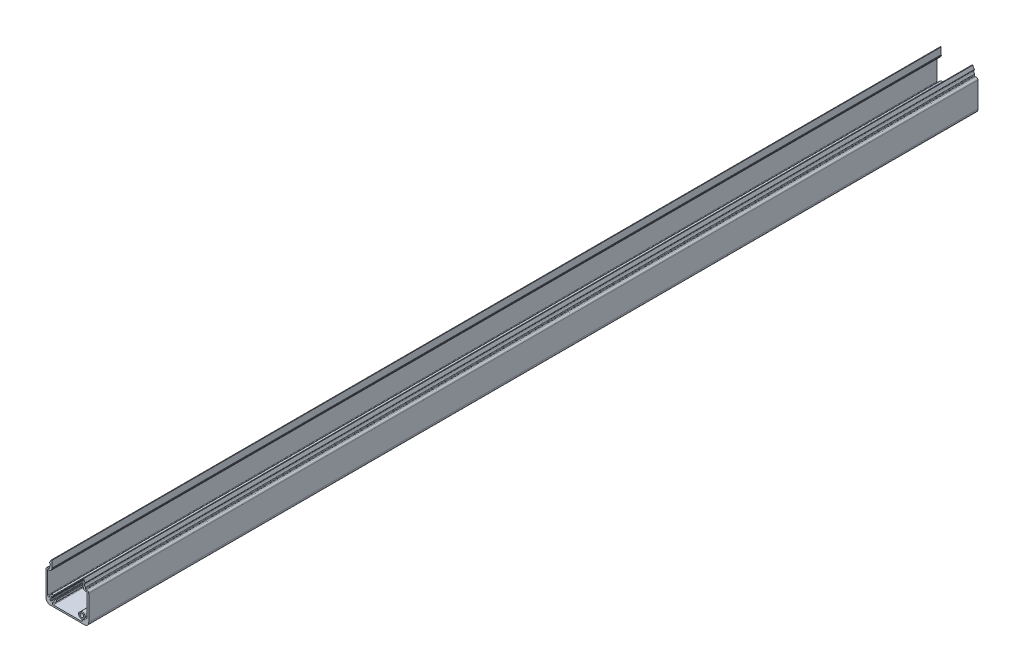
SolidWorks part; units mm, degrees
ref_plane "Front Plane" through (0, 0, 0) normal (0, 0, 1) x (1, 0, 0)
ref_plane "Top Plane" through (0, 0, 0) normal (0, 1, 0) x (1, 0, 0)
ref_plane "Right Plane" through (0, 0, 0) normal (1, 0, 0) x (0, 0, -1)
ref_plane "Plane1" through (0, 0, 20) normal (0, 0, 1) x (1, 0, 0)
sketch "Sketch1" plane through (0, 0, 20) normal (0, 0, 1) x (1, 0, 0)
  line L0 (4, 0) -> (36, 0)
  line L1 (40, 4) -> (40, 27.5)
  line L2 (38.5, 29) -> (37.4085, 29)
  line L3 (36.9085, 29.5) -> (36.9085, 30.572)
  line L4 (36.583, 34.4315) -> (35.1, 37)
  line L5 (35.1, 37) -> (34.5, 37)
  line L6 (34.5, 37) -> (34.5, 30.6727)
  line L7 (34.5, 30.6727) -> (34.1585, 30.5611)
  line L8 (34.1585, 30.5611) -> (34.1585, 29.9899)
  line L9 (34.1585, 29.9899) -> (34.9085, 29.9899)
  line L10 (34.9085, 29.9899) -> (34.9085, 29.7)
  line L11 (36.9085, 27.7) -> (38, 27.7)
  line L12 (38.5, 27.2) -> (38.5, 6.9548)
  line L13 (36.7929, 6.2477) -> (36.6482, 6.3924)
  line L14 (32.7665, 9.2376) -> (33.0471, 8.1904)
  line L15 (35.1484, 5.9123) -> (36.1464, 4.9142)
  line L16 (36.1464, 4.2071) -> (35.7929, 3.8536)
  line L17 (35.0858, 3.8536) -> (34.0877, 4.8516)
  line L18 (31.8096, 6.9529) -> (30.7624, 7.2335)
  line L19 (33.6076, 3.3518) -> (33.7523, 3.2071)
  line L20 (33.0452, 1.5) -> (6.9548, 1.5)
  line L21 (6.2477, 3.2071) -> (6.3924, 3.3518)
  line L22 (9.2376, 7.2335) -> (8.1904, 6.9529)
  line L23 (5.9123, 4.8516) -> (4.9142, 3.8536)
  line L24 (4.2071, 3.8536) -> (3.8536, 4.2071)
  line L25 (3.8536, 4.9142) -> (4.8516, 5.9123)
  line L26 (6.9529, 8.1904) -> (7.2335, 9.2376)
  line L27 (3.3518, 6.3924) -> (3.2071, 6.2477)
  line L28 (1.5, 6.9548) -> (1.5, 27.2)
  line L29 (2, 27.7) -> (3.0915, 27.7)
  line L30 (5.0915, 29.7) -> (5.0915, 29.9899)
  line L31 (5.0915, 29.9899) -> (5.8415, 29.9899)
  line L32 (5.8415, 29.9899) -> (5.8415, 30.5611)
  line L33 (5.8415, 30.5611) -> (5.5, 30.6727)
  line L34 (5.5, 30.6727) -> (5.5, 37)
  line L35 (5.5, 37) -> (4.9, 37)
  line L36 (4.9, 37) -> (3.417, 34.4315)
  line L37 (3.0915, 30.572) -> (3.0915, 29.5)
  line L38 (2.5915, 29) -> (1.5, 29)
  line L39 (0, 27.5) -> (0, 4)
  arc A0 (36, 0) -> (40, 4) centre (36, 4) ccw
  arc A1 (40, 27.5) -> (38.5, 29) centre (38.5, 27.5) ccw
  arc A2 (37.4085, 29) -> (36.9085, 29.5) centre (37.4085, 29.5) cw
  arc A3 (36.9085, 30.572) -> (36.7268, 30.9576) centre (36.4085, 30.572) ccw
  arc A4 (36.7268, 30.9576) -> (36.52, 33.8452) centre (38, 32.5) cw
  arc A5 (36.52, 33.8452) -> (36.583, 34.4315) centre (36.1499, 34.1815) ccw
  arc A6 (34.9085, 29.7) -> (36.9085, 27.7) centre (36.9085, 29.7) ccw
  arc A7 (38, 27.7) -> (38.5, 27.2) centre (38, 27.2) cw
  arc A8 (38.5, 6.9548) -> (36.7929, 6.2477) centre (37.5, 6.9548) cw
  arc A9 (36.6482, 6.3924) -> (33.0095, 9.6116) centre (33.5, 6.5) ccw
  arc A10 (33.0095, 9.6116) -> (32.7665, 9.2376) centre (33.0562, 9.3152) ccw
  arc A11 (33.0471, 8.1904) -> (35.1484, 5.9123) centre (33.5, 6.5) cw
  arc A12 (36.1464, 4.9142) -> (36.1464, 4.2071) centre (35.7929, 4.5607) cw
  arc A13 (35.7929, 3.8536) -> (35.0858, 3.8536) centre (35.4393, 4.2071) cw
  arc A14 (34.0877, 4.8516) -> (31.8096, 6.9529) centre (33.5, 6.5) cw
  arc A15 (30.7624, 7.2335) -> (30.3884, 6.9905) centre (30.6848, 6.9438) ccw
  arc A16 (30.3884, 6.9905) -> (33.6076, 3.3518) centre (33.5, 6.5) ccw
  arc A17 (33.7523, 3.2071) -> (33.0452, 1.5) centre (33.0452, 2.5) cw
  arc A18 (6.9548, 1.5) -> (6.2477, 3.2071) centre (6.9548, 2.5) cw
  arc A19 (6.3924, 3.3518) -> (9.6116, 6.9905) centre (6.5, 6.5) ccw
  arc A20 (9.6116, 6.9905) -> (9.2376, 7.2335) centre (9.3152, 6.9438) ccw
  arc A21 (8.1904, 6.9529) -> (5.9123, 4.8516) centre (6.5, 6.5) cw
  arc A22 (4.9142, 3.8536) -> (4.2071, 3.8536) centre (4.5607, 4.2071) cw
  arc A23 (3.8536, 4.2071) -> (3.8536, 4.9142) centre (4.2071, 4.5607) cw
  arc A24 (4.8516, 5.9123) -> (6.9529, 8.1904) centre (6.5, 6.5) cw
  arc A25 (7.2335, 9.2376) -> (6.9905, 9.6116) centre (6.9438, 9.3152) ccw
  arc A26 (6.9905, 9.6116) -> (3.3518, 6.3924) centre (6.5, 6.5) ccw
  arc A27 (3.2071, 6.2477) -> (1.5, 6.9548) centre (2.5, 6.9548) cw
  arc A28 (1.5, 27.2) -> (2, 27.7) centre (2, 27.2) cw
  arc A29 (3.0915, 27.7) -> (5.0915, 29.7) centre (3.0915, 29.7) ccw
  arc A30 (3.417, 34.4315) -> (3.48, 33.8452) centre (3.8501, 34.1815) ccw
  arc A31 (3.48, 33.8452) -> (3.2732, 30.9576) centre (2, 32.5) cw
  arc A32 (3.2732, 30.9576) -> (3.0915, 30.572) centre (3.5915, 30.572) ccw
  arc A33 (3.0915, 29.5) -> (2.5915, 29) centre (2.5915, 29.5) cw
  arc A34 (1.5, 29) -> (0, 27.5) centre (1.5, 27.5) ccw
  arc A35 (0, 4) -> (4, 0) centre (4, 4) ccw
extrude "Boss-Extrude1" add sketch "Sketch1" against normal blind 832
